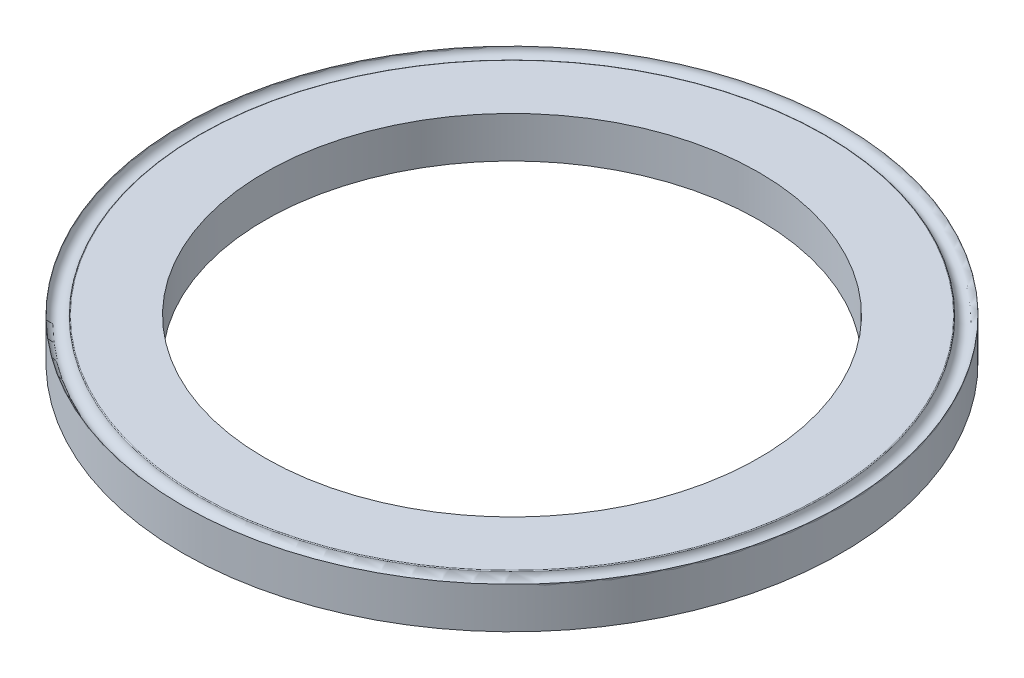
SolidWorks part; units mm, degrees
material "Chrome Stainless Steel"
ref_plane "Front Plane" through (0, 0, 0) normal (0, 0, 1) x (1, 0, 0)
ref_plane "Top Plane" through (0, 0, 0) normal (0, 1, 0) x (1, 0, 0)
ref_plane "Right Plane" through (0, 0, 0) normal (1, 0, 0) x (0, 0, -1)
sketch "Top Sketch" plane through (0, 0, 0) normal (0, 1, 0) x (1, 0, 0)
  circle A0 centre (0, 0) radius 3
  circle A1 centre (0, 0) radius 4
  dimension "InnerDia" = 6
  dimension "Width" = 1
extrude "Top" add sketch "Top Sketch" along normal mid plane 0.5
sketch "Crimp Sketch" plane through (0, 0, 0) normal (0, 0, 1) x (1, 0, 0)
  line L0 (4, 0.25) -> (-4, 0.25) construction
  line L1 (-4, 0.25) -> (-4, -0.25) construction
  line L3 (-4, 0.25) -> (-3.7905, 0.25)
  arc A0 (-4, 0.25) -> (-3.8004, 0.2409) centre (-3.9, 0.25) ccw
  arc A2 (-3.8004, 0.2409) -> (-3.7905, 0.25) centre (-3.7905, 0.24) cw
  dimension "Dia" = 0.2
  dimension "Fillet" = 0.01
revolve "Crimp" cut sketch "Crimp Sketch" angle 360 about axis through (0, 0.25, 0) along (0, -1, 0)
